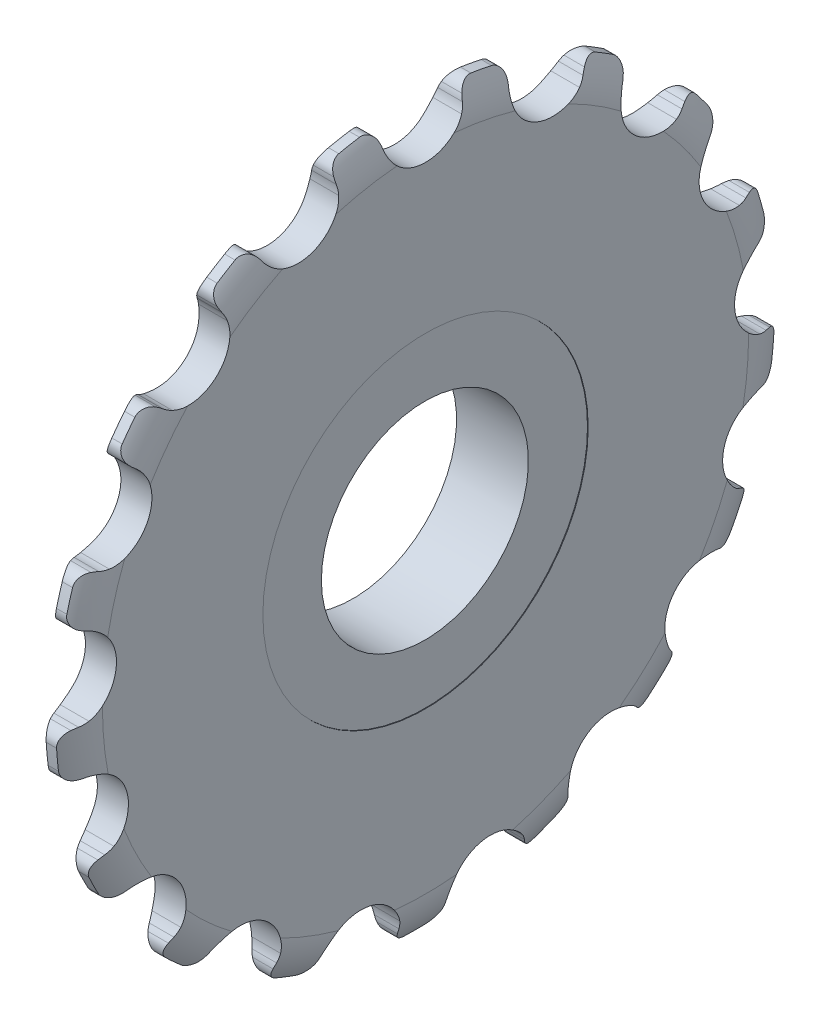
SolidWorks part; units mm, degrees
ref_plane "Plan de face" through (0, 0, 0) normal (0, 0, 1) x (1, 0, 0)
ref_plane "Plan de dessus" through (0, 0, 0) normal (0, 1, 0) x (1, 0, 0)
ref_plane "Plan de droite" through (0, 0, 0) normal (1, 0, 0) x (0, 0, -1)
sketch "Esquisse1" plane through (0, 0, 0) normal (0, 0, 1) x (1, 0, 0)
  line L0 (0, 0) -> (0, 15.714) construction
  line L1 (0, 15.714) -> (0, 17.714)
  line L2 (0, 17.714) -> (1.3778, 17.714)
  line L3 (0, 17.714) -> (0, 19.714) construction
  line L4 (0, 19.714) -> (3.5, 19.714) construction
  line L5 (5, 34.714) -> (6, 34.714)
  line L6 (7, 31.214) -> (7, 15.714)
  line L7 (7, 15.714) -> (0, 15.714)
  line L8 (3.5, 19.714) -> (3.5, 17.714) construction
  line L9 (4, 31.214) -> (7, 31.214) construction
  line L10 (4, 25.714) -> (4, 31.214)
  line L11 (3.5, 19.714) -> (4, 25.714)
  line L12 (5.5, 31.214) -> (5.5, 52.8851) construction
  line L13 (5, 34.714) -> (5, 31.214) construction
  line L14 (6, 34.714) -> (6, 31.214) construction
  line L15 (3.5, 17.714) -> (0, 17.714) construction
  line L16 (0, 0) -> (22.4298, 0) construction
  arc A0 (4, 31.214) -> (5, 34.714) centre (10.625, 31.214) cw
  arc A1 (7, 31.214) -> (6, 34.714) centre (0.375, 31.214) ccw
  arc A2 (3.5, 19.714) -> (3.0218, 18.5074) centre (1.2697, 19.8999) cw
  arc A3 (1.3778, 17.714) -> (3.0218, 18.5074) centre (1.3778, 19.814) ccw
  dimension "D10" = 2.1
  dimension "D1" = 2
  dimension "D2" = 2
  dimension "D3" = 3.5
  dimension "D4" = 0.5
  dimension "D5" = 10
  dimension "D6" = 9
  dimension "D7" = 3
  dimension "D8" = 0.5
  dimension "D9" = 5.5
  dimension "D11" = 15.714
revolve "Révolution1" add sketch "Esquisse1" angle 360 mid plane about L16
sketch "Esquisse4" plane through (7, 0, 0) normal (1, 0, 0) x (0, 0, -1)
  circle A0 centre (0, 0) radius 15.714 construction
  circle A1 centre (0, 0) radius 15.714
sketch "Esquisse7" plane through (7, 0, 0) normal (1, 0, 0) x (0, 0, -1)
  line L0 (0, 0) -> (0, 34.714) construction
  line L1 (0, 0) -> (-4, 0) construction
  line L2 (-4, 0) -> (-4, 36.9371) construction
  line L3 (4, 0) -> (4, 36.9371) construction
  line L4 (6.0637, 32.4381) -> (6.3787, 34.1229) construction
  line L5 (0, 0) -> (-11.2658, 31.6315) construction
  line L6 (6.0637, 32.4381) -> (4.3137, 32.4381) construction
  line L7 (4.3137, 32.4381) -> (4.5761, 34.4111) construction
  circle A0 centre (0, 0) radius 34.714 construction
  arc A1 (8.2811, 31.3293) -> (14.9866, 28.7315) centre (12.2945, 31.7357) ccw
  arc A2 (14.9866, 28.7315) -> (15.5246, 29.3696) centre (12.9844, 30.9657) ccw
  arc A3 (15.5246, 29.3696) -> (15.8597, 29.8061) centre (18.0137, 27.8055) cw
  arc A4 (17.4023, 30.037) -> (15.8597, 29.8061) centre (16.7756, 28.9554) ccw
  arc A5 (19.1312, 28.9665) -> (17.4023, 30.037) centre (0, 0) ccw
  arc A6 (19.1312, 28.9665) -> (19.612, 27.4828) centre (18.4423, 27.9235) cw
  arc A7 (19.3707, 26.9882) -> (19.612, 27.4828) centre (16.8611, 28.5192) ccw
  arc A8 (19.0393, 26.2222) -> (19.3707, 26.9882) centre (21.9317, 25.4258) cw
  arc A9 (19.0393, 26.2222) -> (24.3536, 21.3776) centre (22.9285, 25.1513) ccw
  arc A10 (24.3536, 21.3776) -> (25.0858, 21.7782) centre (23.2937, 24.1841) ccw
  arc A11 (25.0858, 21.7782) -> (25.556, 22.0642) centre (26.8418, 19.4206) cw
  arc A12 (27.0778, 21.7223) -> (25.556, 22.0642) centre (26.1027, 20.9401) ccw
  arc A13 (28.3032, 20.0995) -> (27.0778, 21.7223) centre (0, 0) ccw
  arc A14 (28.3032, 20.0995) -> (28.2156, 18.5422) centre (27.2841, 19.3757) cw
  arc A15 (27.8119, 18.1683) -> (28.2156, 18.5422) centre (26.0248, 20.5025) ccw
  arc A16 (27.2262, 17.5737) -> (27.8119, 18.1683) centre (29.6355, 15.7862) cw
  arc A17 (27.2262, 17.5737) -> (30.4315, 11.1365) centre (30.4659, 15.1702) ccw
  arc A18 (30.4315, 11.1365) -> (31.259, 11.2455) centre (30.4571, 14.1364) ccw
  arc A19 (31.259, 11.2455) -> (31.8007, 11.3423) centre (32.0448, 8.4128) cw
  arc A20 (33.0962, 10.4738) -> (31.8007, 11.3423) centre (31.9045, 10.0967) ccw
  arc A21 (5.3765, 34.2951) -> (4.0216, 33.5226) centre (5.1829, 33.0602) ccw
  arc A22 (-3.5955, 32.2051) -> (3.5955, 32.2051) centre (0, 34.0339) ccw
  arc A23 (33.6527, 8.5179) -> (33.0962, 10.4738) centre (0, 0) ccw
  arc A24 (3.8667, 32.9945) -> (4.0216, 33.5226) centre (6.7528, 32.4352) cw
  arc A25 (3.5955, 32.2051) -> (3.8667, 32.9945) centre (0.9215, 33.5652) ccw
  arc A26 (7.3754, 33.9215) -> (8.3598, 32.7116) centre (7.1098, 32.7) cw
  arc A27 (8.2811, 31.3293) -> (8.3133, 32.1632) centre (11.2658, 31.6315) cw
  arc A28 (8.3133, 32.1632) -> (8.3598, 32.7116) centre (5.4201, 32.6843) ccw
  arc A29 (7.3754, 33.9215) -> (5.3765, 34.2951) centre (0, 0) ccw
  arc A30 (33.6527, 8.5179) -> (33.0085, 7.0975) centre (32.441, 8.2112) cw
  arc A31 (32.4969, 6.8946) -> (33.0085, 7.0975) centre (31.6738, 9.7167) ccw
  arc A32 (31.736, 6.5517) -> (32.4969, 6.8946) centre (33.337, 4.0146) cw
  arc A33 (31.736, 6.5517) -> (32.3995, -0.6087) centre (33.8887, 3.1403) ccw
  arc A34 (32.3995, -0.6087) -> (33.2105, -0.8059) centre (33.507, 2.1794) ccw
  arc A35 (33.2105, -0.8059) -> (33.7506, -0.9113) centre (32.9199, -3.7313) cw
  arc A36 (34.6449, -2.1892) -> (33.7506, -0.9113) centre (33.3974, -2.1104) ccw
  arc A37 (34.4573, -4.214) -> (34.6449, -2.1892) centre (0, 0) ccw
  arc A38 (34.4573, -4.214) -> (33.3434, -5.3058) centre (33.2165, -4.0623) cw
  arc A39 (32.7931, -5.3102) -> (33.3434, -5.3058) centre (33.045, -2.3813) ccw
  arc A40 (31.9597, -5.3551) -> (32.7931, -5.3102) centre (32.536, -8.2992) cw
  arc A41 (31.9597, -5.3551) -> (29.9918, -12.2716) centre (32.7347, -9.3138) ccw
  arc A42 (29.9918, -12.2716) -> (30.6767, -12.7485) centre (32.0317, -10.0719) ccw
  arc A43 (30.6767, -12.7485) -> (31.1423, -13.0419) centre (29.349, -15.3713) cw
  arc A44 (31.5146, -14.5566) -> (31.1423, -13.0419) centre (30.3798, -14.0324) ccw
  arc A45 (30.6082, -16.3769) -> (31.5146, -14.5566) centre (0, 0) ccw
  arc A46 (30.6082, -16.3769) -> (29.1751, -16.9926) centre (29.506, -15.7872) cw
  arc A47 (28.6604, -16.7979) -> (29.1751, -16.9926) centre (29.9533, -14.1577) ccw
  arc A48 (27.8671, -16.5386) -> (28.6604, -16.7979) centre (27.3409, -19.4921) cw
  arc A49 (27.8671, -16.5386) -> (23.5335, -22.2772) centre (27.1596, -20.51) ccw
  arc A50 (23.5335, -22.2772) -> (23.9999, -22.9693) centre (26.2302, -20.9629) ccw
  arc A51 (23.9999, -22.9693) -> (24.328, -23.4111) centre (21.8144, -24.9354) cw
  arc A52 (24.128, -24.958) -> (24.328, -23.4111) centre (23.2592, -24.0593) ccw
  arc A53 (22.6252, -26.3279) -> (24.128, -24.958) centre (0, 0) ccw
  arc A54 (22.6252, -26.3279) -> (21.0665, -26.3844) centre (21.8105, -25.3799) cw
  arc A55 (20.6569, -26.0169) -> (21.0665, -26.3844) centre (22.8163, -24.0221) ccw
  arc A56 (20.0108, -25.4886) -> (20.6569, -26.0169) centre (18.4533, -28.0526) cw
  arc A57 (20.0108, -25.4886) -> (13.8968, -29.2742) centre (17.9165, -28.9362) ccw
  arc A58 (13.8968, -29.2742) -> (14.0818, -30.088) centre (16.8863, -29.0228) ccw
  arc A59 (14.0818, -30.088) -> (14.2282, -30.6185) centre (11.3336, -31.1318) cw
  arc A60 (13.4829, -31.9887) -> (14.2282, -30.6185) centre (12.9974, -30.8368) ccw
  arc A61 (11.5867, -32.7232) -> (13.4829, -31.9887) centre (0, 0) ccw
  arc A62 (11.5867, -32.7232) -> (10.1128, -32.2128) centre (11.1694, -31.5449) cw
  arc A63 (9.8636, -31.7221) -> (10.1128, -32.2128) centre (12.5978, -30.6421) ccw
  arc A64 (9.452, -30.9961) -> (9.8636, -31.7221) centre (7.0734, -32.8243) cw
  arc A65 (9.452, -30.9961) -> (2.3834, -32.3175) centre (6.2537, -33.4544) ccw
  arc A66 (2.3834, -32.3175) -> (2.2618, -33.1432) centre (5.2617, -33.163) ccw
  arc A67 (2.2618, -33.1432) -> (2.2067, -33.6907) centre (-0.6779, -33.1237) cw
  arc A68 (1.0168, -34.6991) -> (2.2067, -33.6907) centre (0.9801, -33.4496) ccw
  arc A69 (-1.0168, -34.6991) -> (1.0168, -34.6991) centre (0, 0) ccw
  arc A70 (-1.0168, -34.6991) -> (-2.2067, -33.6907) centre (-0.9801, -33.4496) cw
  arc A71 (-2.2618, -33.1432) -> (-2.2067, -33.6907) centre (0.6779, -33.1237) ccw
  arc A72 (-2.3834, -32.3175) -> (-2.2618, -33.1432) centre (-5.2617, -33.163) cw
  arc A73 (-2.3834, -32.3175) -> (-9.452, -30.9961) centre (-6.2537, -33.4544) ccw
  arc A74 (-9.452, -30.9961) -> (-9.8636, -31.7221) centre (-7.0734, -32.8243) ccw
  arc A75 (-9.8636, -31.7221) -> (-10.1128, -32.2128) centre (-12.5978, -30.6421) cw
  arc A76 (-11.5867, -32.7232) -> (-10.1128, -32.2128) centre (-11.1694, -31.5449) ccw
  arc A77 (-13.4829, -31.9887) -> (-11.5867, -32.7232) centre (0, 0) ccw
  arc A78 (-13.4829, -31.9887) -> (-14.2282, -30.6185) centre (-12.9974, -30.8368) cw
  arc A79 (-14.0818, -30.088) -> (-14.2282, -30.6185) centre (-11.3336, -31.1318) ccw
  arc A80 (-13.8968, -29.2742) -> (-14.0818, -30.088) centre (-16.8863, -29.0228) cw
  arc A81 (-13.8968, -29.2742) -> (-20.0108, -25.4886) centre (-17.9165, -28.9362) ccw
  arc A82 (-20.0108, -25.4886) -> (-20.6569, -26.0169) centre (-18.4533, -28.0526) ccw
  arc A83 (-20.6569, -26.0169) -> (-21.0665, -26.3844) centre (-22.8163, -24.0221) cw
  arc A84 (-22.6252, -26.3279) -> (-21.0665, -26.3844) centre (-21.8105, -25.3799) ccw
  arc A85 (-24.128, -24.958) -> (-22.6252, -26.3279) centre (0, 0) ccw
  arc A86 (-24.128, -24.958) -> (-24.328, -23.4111) centre (-23.2592, -24.0593) cw
  arc A87 (-23.9999, -22.9693) -> (-24.328, -23.4111) centre (-21.8144, -24.9354) ccw
  arc A88 (-23.5335, -22.2772) -> (-23.9999, -22.9693) centre (-26.2302, -20.9629) cw
  arc A89 (-23.5335, -22.2772) -> (-27.8671, -16.5386) centre (-27.1596, -20.51) ccw
  arc A90 (-27.8671, -16.5386) -> (-28.6604, -16.7979) centre (-27.3409, -19.4921) ccw
  arc A91 (-28.6604, -16.7979) -> (-29.1751, -16.9926) centre (-29.9533, -14.1577) cw
  arc A92 (-30.6082, -16.3769) -> (-29.1751, -16.9926) centre (-29.506, -15.7872) ccw
  arc A93 (-31.5146, -14.5566) -> (-30.6082, -16.3769) centre (0, 0) ccw
  arc A94 (-31.5146, -14.5566) -> (-31.1423, -13.0419) centre (-30.3798, -14.0324) cw
  arc A95 (-30.6767, -12.7485) -> (-31.1423, -13.0419) centre (-29.349, -15.3713) ccw
  arc A96 (-29.9918, -12.2716) -> (-30.6767, -12.7485) centre (-32.0317, -10.0719) cw
  arc A97 (-29.9918, -12.2716) -> (-31.9597, -5.3551) centre (-32.7347, -9.3138) ccw
  arc A98 (-31.9597, -5.3551) -> (-32.7931, -5.3102) centre (-32.536, -8.2992) ccw
  arc A99 (-32.7931, -5.3102) -> (-33.3434, -5.3058) centre (-33.045, -2.3813) cw
  arc A100 (-34.4573, -4.214) -> (-33.3434, -5.3058) centre (-33.2165, -4.0623) ccw
  arc A101 (-34.6449, -2.1892) -> (-34.4573, -4.214) centre (0, 0) ccw
  arc A102 (-34.6449, -2.1892) -> (-33.7506, -0.9113) centre (-33.3974, -2.1104) cw
  arc A103 (-33.2105, -0.8059) -> (-33.7506, -0.9113) centre (-32.9199, -3.7313) ccw
  arc A104 (-32.3995, -0.6087) -> (-33.2105, -0.8059) centre (-33.507, 2.1794) cw
  arc A105 (-32.3995, -0.6087) -> (-31.736, 6.5517) centre (-33.8887, 3.1403) ccw
  arc A106 (-31.736, 6.5517) -> (-32.4969, 6.8946) centre (-33.337, 4.0146) ccw
  arc A107 (-32.4969, 6.8946) -> (-33.0085, 7.0975) centre (-31.6738, 9.7167) cw
  arc A108 (-33.6527, 8.5179) -> (-33.0085, 7.0975) centre (-32.441, 8.2112) ccw
  arc A109 (-33.0962, 10.4738) -> (-33.6527, 8.5179) centre (0, 0) ccw
  arc A110 (-33.0962, 10.4738) -> (-31.8007, 11.3423) centre (-31.9045, 10.0967) cw
  arc A111 (-31.259, 11.2455) -> (-31.8007, 11.3423) centre (-32.0448, 8.4128) ccw
  arc A112 (-30.4315, 11.1365) -> (-31.259, 11.2455) centre (-30.4571, 14.1364) cw
  arc A113 (-30.4315, 11.1365) -> (-27.2262, 17.5737) centre (-30.4659, 15.1702) ccw
  arc A114 (-27.2262, 17.5737) -> (-27.8119, 18.1683) centre (-29.6355, 15.7862) ccw
  arc A115 (-27.8119, 18.1683) -> (-28.2156, 18.5422) centre (-26.0248, 20.5025) cw
  arc A116 (-28.3032, 20.0995) -> (-28.2156, 18.5422) centre (-27.2841, 19.3757) ccw
  arc A117 (-27.0778, 21.7223) -> (-28.3032, 20.0995) centre (0, 0) ccw
  arc A118 (-27.0778, 21.7223) -> (-25.556, 22.0642) centre (-26.1027, 20.9401) cw
  arc A119 (-25.0858, 21.7782) -> (-25.556, 22.0642) centre (-26.8418, 19.4206) ccw
  arc A120 (-24.3536, 21.3776) -> (-25.0858, 21.7782) centre (-23.2937, 24.1841) cw
  arc A121 (-24.3536, 21.3776) -> (-19.0393, 26.2222) centre (-22.9285, 25.1513) ccw
  arc A122 (-19.0393, 26.2222) -> (-19.3707, 26.9882) centre (-21.9317, 25.4258) ccw
  arc A123 (-19.3707, 26.9882) -> (-19.612, 27.4828) centre (-16.8611, 28.5192) cw
  arc A124 (-19.1312, 28.9665) -> (-19.612, 27.4828) centre (-18.4423, 27.9235) ccw
  arc A125 (-17.4023, 30.037) -> (-19.1312, 28.9665) centre (0, 0) ccw
  arc A126 (-17.4023, 30.037) -> (-15.8597, 29.8061) centre (-16.7756, 28.9554) cw
  arc A127 (-15.5246, 29.3696) -> (-15.8597, 29.8061) centre (-18.0137, 27.8055) ccw
  arc A128 (-14.9866, 28.7315) -> (-15.5246, 29.3696) centre (-12.9844, 30.9657) cw
  arc A129 (-14.9866, 28.7315) -> (-8.2811, 31.3293) centre (-12.2945, 31.7357) ccw
  arc A130 (-8.2811, 31.3293) -> (-8.3133, 32.1632) centre (-11.2658, 31.6315) ccw
  arc A131 (-8.3133, 32.1632) -> (-8.3598, 32.7116) centre (-5.4201, 32.6843) cw
  arc A132 (-7.3754, 33.9215) -> (-8.3598, 32.7116) centre (-7.1098, 32.7) ccw
  arc A133 (-5.3765, 34.2951) -> (-7.3754, 33.9215) centre (0, 0) ccw
  arc A134 (-5.3765, 34.2951) -> (-4.0216, 33.5226) centre (-5.1829, 33.0602) cw
  arc A135 (-3.8667, 32.9945) -> (-4.0216, 33.5226) centre (-6.7528, 32.4352) ccw
  arc A136 (-3.5955, 32.2051) -> (-3.8667, 32.9945) centre (-0.9215, 33.5652) cw
  circle A137 centre (0, 0) radius 46.4666
  dimension "D1" = 17
  dimension "D6" = 3
  dimension "D3" = 4
  dimension "D5" = 1.75
extrude "Enlèv. mat.-Extru.1" cut sketch "Esquisse7" against normal through all contours A97 A98 A99 A100 A101 A102 A103 A104 A105 A106 A107 A108 A109 A110 A111 A112 A113 A114 A115 A116 A117 A118 A119 A120 A121 A122 A123 A124 A125 A126 A127 A128 A129 A130 A131 A132 A133 A134 A135 A136 A22 A25 A24 A21 A29 A26 A28 A27 A1 A2 A3 A4 A5 A6 A7 A8 A9 A10 A11 A12 A13 A14 A15 A16 A17 A18 A19 A20 A23 A30 A31 A32 A33 A34 A35 A36 A37 A38 A39 A40 A41 A42 A43 A44 A45 A46 A47 A48 A49 A50 A51 A52 A53 A54 A55 A56 A57 A58 A59 A60 A61 A62 A63 A64 A65 A66 A67 A68 A69 A70 A71 A72 A73 A74 A75 A76 A77 A78 A79 A80 A81 A82 A83 A84 A85 A86 A87 A88 A89 A90 A91 A92 A93 A94 A95 A96 | A137
fillet "Congé1" radius 0.25 1 edges at (0, 0, 17.714)
sketch "Sketch1" plane through (0, 0, 0) normal (1, 0, 0) x (0, 0, -1)
sketch "Sketch3" plane through (0, 0, 0) normal (0, 0, 1) x (1, 0, 0)
  line L1 (0, 15.71) -> (6.94, 15.71)
  line L2 (0, 15.71) -> (0, 10)
  line L3 (0, 10) -> (6.94, 10)
  line L4 (6.94, 15.71) -> (6.94, 10)
  line L5 (0, 0) -> (6.94, 0) construction
  dimension "D1" = 10
  dimension "D2" = 5.71
  dimension "D3" = 6.94
revolve "Revolve1" add sketch "Sketch3" angle 360 about L5
